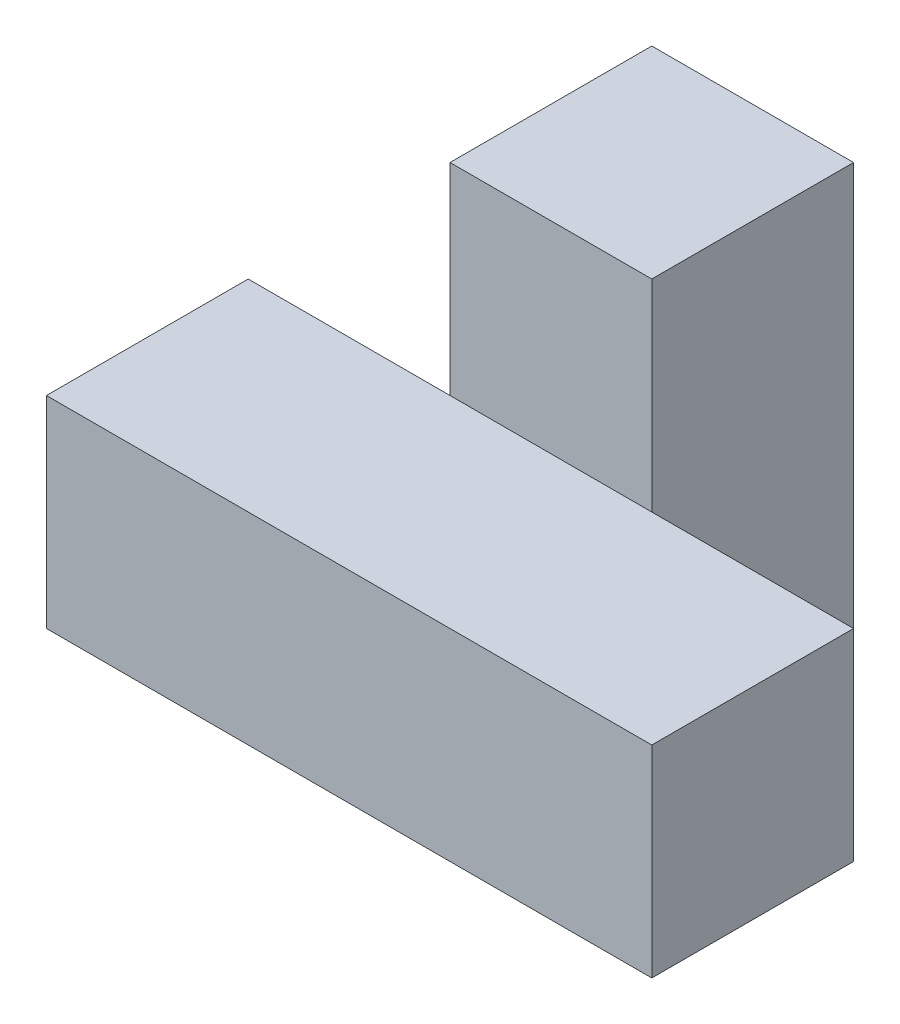
SolidWorks part; units mm, degrees
ref_plane "Front Plane" through (0, 0, 0) normal (0, 0, 1) x (1, 0, 0)
ref_plane "Top Plane" through (0, 0, 0) normal (0, 1, 0) x (1, 0, 0)
ref_plane "Right Plane" through (0, 0, 0) normal (1, 0, 0) x (0, 0, -1)
sketch "Sketch2" plane through (0, 0, 0) normal (0, 1, 0) x (1, 0, 0)
  line L0 (0, 0) -> (25.4, 0)
  line L1 (25.4, 0) -> (25.4, 25.4)
  line L2 (25.4, 25.4) -> (50.8, 25.4)
  line L3 (50.8, 25.4) -> (50.8, 0)
  line L4 (50.8, 0) -> (76.2, 0)
  line L5 (76.2, 0) -> (76.2, -25.4)
  line L6 (76.2, -25.4) -> (0, -25.4)
  line L7 (0, -25.4) -> (0, 0)
  dimension "D1" = 25.4
  dimension "D2" = 25.4
  dimension "D3" = 25.4
  dimension "D4" = 25.4
  dimension "D5" = 76.2
extrude "Boss-Extrude2" add sketch "Sketch2" along normal blind 25.4
sketch "Sketch3" plane through (0, 25.4, 0) normal (0, 1, 0) x (1, 0, 0)
  line L1 (25.4, 25.4) -> (50.8, 25.4)
  line L2 (25.4, 25.4) -> (25.4, 0)
  line L3 (25.4, 0) -> (50.8, 0)
  line L4 (50.8, 25.4) -> (50.8, 0)
extrude "Boss-Extrude3" add sketch "Sketch3" along normal blind 25.4
